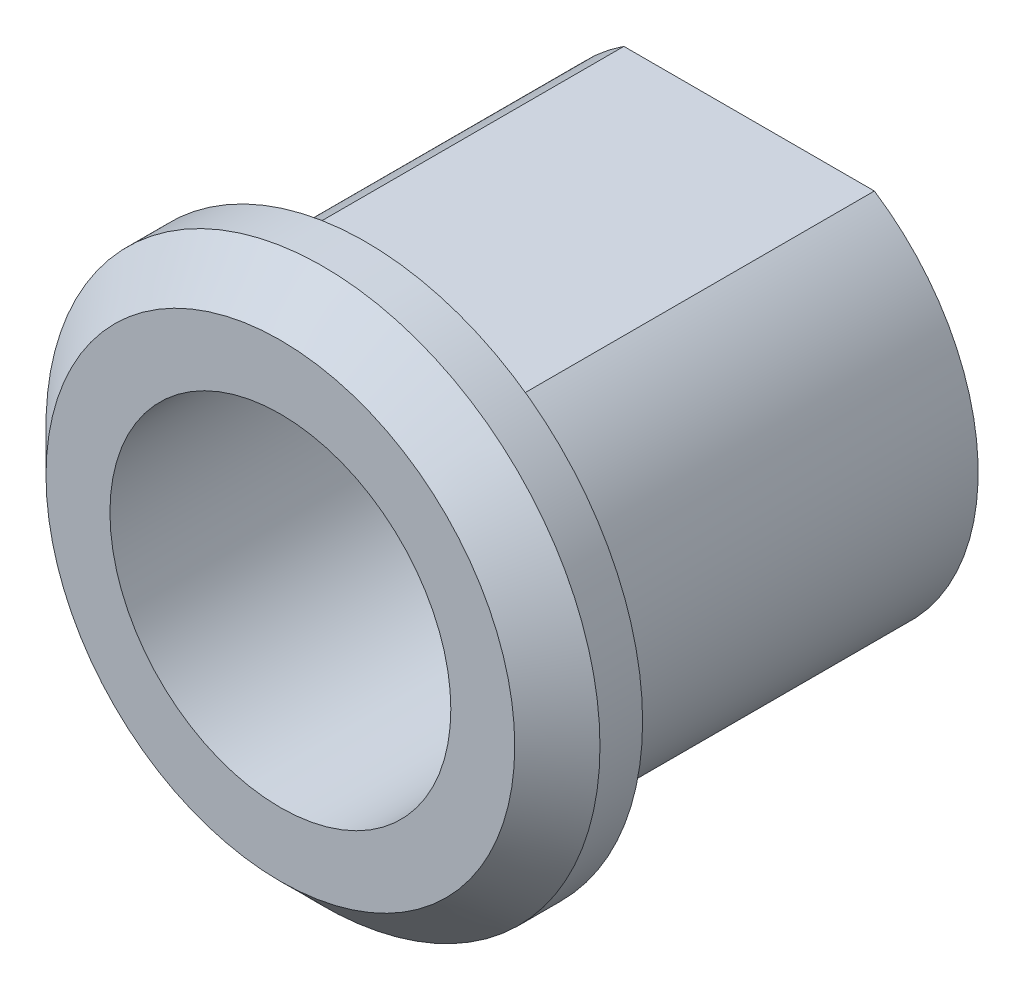
SolidWorks part; units mm, degrees
ref_plane "Front Plane" through (0, 0, 0) normal (0, 0, 1) x (1, 0, 0)
ref_plane "Top Plane" through (0, 0, 0) normal (0, 1, 0) x (1, 0, 0)
ref_plane "Right Plane" through (0, 0, 0) normal (1, 0, 0) x (0, 0, -1)
sketch "Sketch1" plane through (0, 0, 0) normal (0, 0, 1) x (1, 0, 0)
  circle A0 centre (0, 0) radius 13
  circle A1 centre (0, 0) radius 8
  dimension "D1" = 26
  dimension "D2" = 16
extrude "Boss-Extrude1" add sketch "Sketch1" along normal blind 4
sketch "Sketch2" plane through (0, 0, 0) normal (0, 0, -1) x (-1, 0, 0)
  line L0 (-5.879, 9) -> (5.879, 9)
  line L1 (0, 0) -> (20.7187, 0) construction
  line L2 (-5.879, -9) -> (5.879, -9)
  arc A0 (5.879, -9) -> (5.879, 9) centre (0, 0) ccw
  arc A1 (-5.879, 9) -> (-5.879, -9) centre (0, 0) ccw
  dimension "D1" = 21.5
  dimension "D2" = 9
extrude "Boss-Extrude2" add sketch "Sketch2" along normal blind 18
sketch "Sketch3" plane through (0, 0, 0) normal (0, 0, 1) x (1, 0, 0)
  circle A1 centre (0, 0) radius 8
  circle A2 centre (0, 0) radius 8
  dimension "D1" = 0
extrude "Cut-Extrude1" cut sketch "Sketch3" against normal blind 18
chamfer "Chamfer1" distance 2 angle 45 1 edges at (13, 0, 4)
